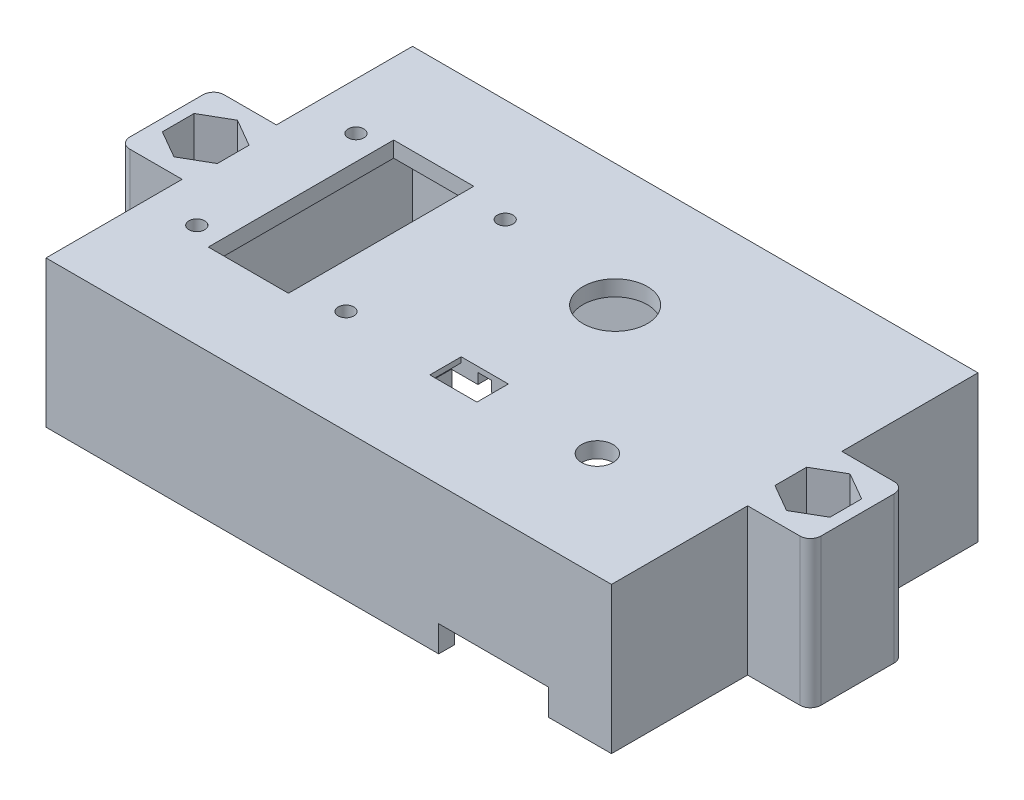
SolidWorks part; units mm, degrees
ref_plane "Front Plane" through (0, 0, 0) normal (0, 0, 1) x (1, 0, 0)
ref_plane "Top Plane" through (0, 0, 0) normal (0, 1, 0) x (1, 0, 0)
ref_plane "Right Plane" through (0, 0, 0) normal (1, 0, 0) x (0, 0, -1)
sketch "Sketch2" plane through (0, 0, 0) normal (0, 1, 0) x (1, 0, 0)
  line L0 (-37.0384, 33.0848) -> (37.9616, -5.9152) construction
  line L1 (-57.0384, 38.0848) -> (42.9616, 38.0848) construction
  line L2 (-57.0384, 38.0848) -> (-57.0384, -23.9152) construction
  line L3 (-57.0384, -23.9152) -> (42.9616, -23.9152) construction
  line L4 (42.9616, 38.0848) -> (42.9616, -23.9152) construction
  line L5 (-37.0384, -5.9152) -> (37.9616, 33.0848) construction
  line L6 (-57.0384, 7.0848) -> (-42.7957, 7.0848) construction
  line L7 (-58.0384, 39.0848) -> (43.9616, 39.0848) construction
  line L8 (-58.0384, 39.0848) -> (-58.0384, -24.9152) construction
  line L9 (-58.0384, -24.9152) -> (43.9616, -24.9152) construction
  line L10 (43.9616, 39.0848) -> (43.9616, -24.9152) construction
  line L11 (-61.0384, 42.0848) -> (46.9616, 42.0848)
  line L12 (-61.0384, 42.0848) -> (-61.0384, -27.9152)
  line L13 (-61.0384, -27.9152) -> (46.9616, -27.9152)
  line L14 (46.9616, 42.0848) -> (46.9616, -27.9152)
  line L15 (-25.0384, 0.0848) -> (-17.0384, 0.0848) construction
  line L16 (-25.0384, 0.0848) -> (-25.0384, -14.4152) construction
  line L17 (-25.0384, -14.4152) -> (-17.0384, -14.4152) construction
  line L18 (-17.0384, 0.0848) -> (-17.0384, -14.4152) construction
  line L19 (-19.0384, 3.5848) -> (-15.0384, 3.5848) construction
  line L20 (-19.0384, 3.5848) -> (-19.0384, 1.5848) construction
  line L21 (-19.0384, 1.5848) -> (-15.0384, 1.5848) construction
  line L22 (-15.0384, 3.5848) -> (-15.0384, 1.5848) construction
  line L23 (-17.0384, 1.5848) -> (-15.0384, 1.5848) construction
  line L24 (-17.0384, 1.5848) -> (-17.0384, -8.4152) construction
  line L25 (-17.0384, -8.4152) -> (-15.0384, -8.4152) construction
  line L26 (-15.0384, 1.5848) -> (-15.0384, -8.4152) construction
  line L28 (-54.5384, -10.6152) -> (-21.0384, -10.6152) construction
  line L29 (-54.5384, -10.6152) -> (-54.5384, 24.7848) construction
  line L30 (-54.5384, 24.7848) -> (-21.0384, 24.7848) construction
  line L31 (-21.0384, -10.6152) -> (-21.0384, 24.7848) construction
  point P4 (-37.0384, 33.0848)
  point P5 (37.9616, 33.0848)
  point P6 (37.9616, -5.9152)
  point P7 (-37.0384, -5.9152)
  point P9 (20.4616, 5.5848)
  point P28 (-54.5384, 7.0848)
  point P38 (-37.0384, 33.0848)
  dimension "D11" = 1.5
  dimension "D12" = 2
  dimension "D1" = 62
  dimension "D2" = 100
  dimension "D3" = 5
  dimension "D4" = 20
  dimension "D5" = 5
  dimension "D6" = 5
  dimension "D7" = 18
  dimension "D8" = 20
  dimension "D9" = 18
  dimension "D10" = 5
  dimension "D13" = 2
  dimension "D14" = 1
  dimension "D15" = 3
  dimension "D16" = 1
  dimension "D17" = 3
  dimension "D18" = 1
  dimension "D19" = 3
  dimension "D20" = 1
  dimension "D21" = 3
  dimension "D22" = 10.5
  dimension "D23" = 33
  dimension "D24" = 61
  dimension "D25" = 39
  dimension "D26" = 4
  dimension "D27" = 10
  dimension "D28" = 35.4
  dimension "D29" = 33.5
  dimension "D30" = 2.5
extrude "Boss-Extrude1" add sketch "Sketch2" along normal blind 3
sketch "Sketch7" plane through (0, 0, 0) normal (0, -1, 0) x (-1, 0, 0)
  line L0 (57.0384, -23.9152) -> (-42.9616, -23.9152) construction
  line L1 (55.0384, -14.9152) -> (58.0384, -14.9152) construction
  line L2 (58.0384, 39.0848) -> (-43.9616, 39.0848)
  line L3 (58.0384, 39.0848) -> (58.0384, -24.9152)
  line L4 (58.0384, -24.9152) -> (-43.9616, -24.9152)
  line L5 (-43.9616, 39.0848) -> (-43.9616, -24.9152)
  line L6 (61.0384, 42.0848) -> (-46.9616, 42.0848)
  line L7 (61.0384, 42.0848) -> (61.0384, -27.9152)
  line L8 (61.0384, -27.9152) -> (-46.9616, -27.9152)
  line L9 (-46.9616, 42.0848) -> (-46.9616, -27.9152)
  line L10 (55.0384, -14.9152) -> (55.0384, -24.9152) construction
  line L11 (55.0384, -24.9152) -> (58.0384, -24.9152) construction
  line L12 (58.0384, -14.9152) -> (58.0384, -24.9152) construction
  line L13 (47.0384, -21.9152) -> (55.0384, -21.9152) construction
  line L14 (47.0384, -21.9152) -> (47.0384, -24.9152) construction
  line L15 (47.0384, -24.9152) -> (55.0384, -24.9152) construction
  line L16 (55.0384, -21.9152) -> (55.0384, -24.9152) construction
  line L17 (57.0384, 38.0848) -> (57.0384, -23.9152) construction
  dimension "D1" = 2
  dimension "D2" = 2
  dimension "D3" = 8
  dimension "D4" = 10
extrude "Boss-Extrude4" add sketch "Sketch7" along normal blind 25 contours L7 L6 L9 L8
sketch "Sketch16" plane through (0, 0, 0) normal (0, -1, 0) x (1, 0, 0)
  line L1 (-17.0384, 8.4152) -> (-15.0384, 8.4152)
  line L2 (-17.0384, 8.4152) -> (-17.0384, -1.5848)
  line L3 (-17.0384, -1.5848) -> (-15.0384, -1.5848)
  line L4 (-15.0384, 8.4152) -> (-15.0384, -1.5848)
  line L5 (-15.0384, -1.5848) -> (-19.0384, -1.5848)
  line L6 (-15.0384, -1.5848) -> (-15.0384, -3.5848)
  line L7 (-15.0384, -3.5848) -> (-19.0384, -3.5848)
  line L8 (-19.0384, -1.5848) -> (-19.0384, -3.5848)
  line L9 (-55.0384, 14.9152) -> (-58.0384, 14.9152)
  line L10 (-55.0384, 14.9152) -> (-55.0384, 24.9152)
  line L11 (-55.0384, 24.9152) -> (-58.0384, 24.9152)
  line L12 (-58.0384, 14.9152) -> (-58.0384, 24.9152)
  line L13 (-55.0384, 21.9152) -> (-47.0384, 21.9152)
  line L14 (-55.0384, 21.9152) -> (-55.0384, 24.9152)
  line L15 (-55.0384, 24.9152) -> (-47.0384, 24.9152)
  line L16 (-47.0384, 21.9152) -> (-47.0384, 24.9152)
  line M7 (43.9616, 24.9152) -> (-58.0384, 24.9152)
  line M8 (-58.0384, 24.9152) -> (-58.0384, -39.0848)
extrude "Boss-Extrude5" add sketch "Sketch16" along normal offset from surface (22.8 mm away) 2.2 contours L4 L1 L2 L3 | L9 L10 M7 M8 | L13 L16 L10 M7 | L6 L7 L8 L5 up to face at (-7.0384, -25, -7.0848)
sketch "Sketch19" plane through (0, 0, 0) normal (0, -1, 0) x (1, 0, 0)
  line L1 (-55.5384, 2.6152) -> (-49.5384, 2.6152)
  line L2 (-55.5384, 2.6152) -> (-55.5384, -16.7848)
  line L3 (-55.5384, -16.7848) -> (-49.5384, -16.7848)
  line L4 (-49.5384, 2.6152) -> (-49.5384, -16.7848)
  line L5 (-57.0384, -7.0848) -> (-42.7957, -7.0848) construction
  line L6 (-54.5384, -24.7848) -> (-21.0384, -24.7848) construction
  line L7 (-54.5384, 10.6152) -> (-54.5384, -24.7848) construction
  point P6 (-55.5384, -7.0848)
  dimension "D1" = 8
  dimension "D2" = 6
  dimension "D3" = 5
extrude "Cut-Extrude10" cut sketch "Sketch19" against normal blind 1
sketch "Sketch18" plane through (0, 0, 0) normal (0, -1, 0) x (1, 0, 0)
  line L0 (-54.5384, 10.6152) -> (-54.5384, -24.7848) construction
  line L1 (-47.3384, -24.7848) -> (-32.0384, -24.7848)
  line L2 (-47.3384, -24.7848) -> (-47.3384, 10.6152)
  line L3 (-47.3384, 10.6152) -> (-32.0384, 10.6152)
  line L4 (-32.0384, -24.7848) -> (-32.0384, 10.6152)
  line L5 (-21.0384, 10.6152) -> (-21.0384, -24.7848) construction
  line L6 (-54.5384, -24.7848) -> (-21.0384, -24.7848) construction
  line L7 (-54.5384, 10.6152) -> (-21.0384, 10.6152) construction
  line L8 (-47.3384, -7.0848) -> (-57.0384, -7.0848) construction
  circle A0 centre (-52.0384, -22.2848) radius 1.5
  circle A1 centre (-23.5384, -22.2848) radius 1.5
  circle A2 centre (-23.5384, 8.1152) radius 1.5
  circle A3 centre (-52.0384, 8.1152) radius 1.5
  point P18 (-52.0384, 8.1152)
  point P19 (-23.5384, -22.2848)
  dimension "D3" = 2.5
  dimension "D5" = 3
  dimension "D1" = 7.2
  dimension "D2" = 11
  dimension "D4" = 2.5
  dimension "D6" = 2.5
  dimension "D7" = 2.5
  dimension "D8" = 2
  dimension "D9" = 2
extrude "Cut-Extrude9" cut sketch "Sketch18" against normal through all
sketch "Sketch20" plane through (0, 0, 0) normal (0, -1, 0) x (1, 0, 0)
  line L0 (-49.5384, 2.6152) -> (-55.5384, 2.6152) construction
  line L1 (-55.5384, 12.6152) -> (-49.5384, 12.6152)
  line L2 (-55.5384, 12.6152) -> (-55.5384, 2.6152)
  line L3 (-55.5384, 2.6152) -> (-49.5384, 2.6152)
  line L4 (-49.5384, 12.6152) -> (-49.5384, 2.6152)
  line L5 (-54.5384, 10.6152) -> (-54.5384, -24.7848) construction
  line L6 (-49.5384, -7.0848) -> (-56.0913, -7.0848) construction
  line L7 (-49.5384, -16.7848) -> (-49.5384, 2.6152) construction
  line L8 (-55.5384, -16.7848) -> (-49.5384, -16.7848)
  line L9 (-49.5384, -26.7848) -> (-49.5384, -16.7848)
  line L10 (-55.5384, -26.7848) -> (-49.5384, -26.7848)
  line L11 (-55.5384, -26.7848) -> (-55.5384, -16.7848)
  line L12 (-52.0384, 8.1152) -> (-23.5384, 8.1152) construction
  line L13 (-37.7884, 8.1152) -> (-37.7884, 15.0987) construction
  line L14 (-20.0384, -26.7848) -> (-20.0384, -16.7848)
  line L15 (-20.0384, -26.7848) -> (-26.0384, -26.7848)
  line L16 (-26.0384, -26.7848) -> (-26.0384, -16.7848)
  line L17 (-20.0384, -16.7848) -> (-26.0384, -16.7848)
  line L18 (-20.0384, 2.6152) -> (-26.0384, 2.6152)
  line L19 (-26.0384, 12.6152) -> (-26.0384, 2.6152)
  line L20 (-20.0384, 12.6152) -> (-26.0384, 12.6152)
  line L21 (-20.0384, 12.6152) -> (-20.0384, 2.6152)
  circle A0 centre (-52.0384, 8.1152) radius 1.5
  circle A1 centre (-23.5384, 8.1152) radius 2
  circle A2 centre (-52.0384, -22.2848) radius 2
  circle A3 centre (-23.5384, -22.2848) radius 2
  circle A4 centre (-52.0384, 8.1152) radius 1.5 construction
  dimension "D1" = 10
  dimension "D2" = 6
  dimension "D3" = 5
extrude "Boss-Extrude6" add sketch "Sketch20" along normal blind 1.5
sketch "Sketch21" plane through (0, 3, 0) normal (0, -1, 0) x (1, 0, 0)
  line L4 (-54.5384, 10.6152) -> (-21.0384, 10.6152) construction
  line L5 (-5.0384, 4.6152) -> (3.9616, 4.6152)
  line L6 (-5.0384, 4.6152) -> (-5.0384, 10.6152)
  line L7 (-5.0384, 10.6152) -> (3.9616, 10.6152)
  line L8 (3.9616, 4.6152) -> (3.9616, 10.6152)
  line L11 (-15.0384, -1.5848) -> (-15.0384, 8.4152) construction
  line L12 (-54.5384, -24.7848) -> (-21.0384, -24.7848) construction
  circle A0 centre (1.1116, -18.6348) radius 6.15
  circle A2 centre (23.9616, 7.6152) radius 3
  dimension "D1" = 12.3
  dimension "D5" = 20
  dimension "D2" = 6
  dimension "D3" = 9
  dimension "D4" = 10
extrude "Cut-Extrude11" cut sketch "Sketch21" along normal blind 1 contours L5 L8 L7 L6
sketch "Sketch23" plane through (0, 0, 0) normal (0, -1, 0) x (1, 0, 0)
  line L0 (-0.5384, 10.6152) -> (-0.5384, 4.6152) construction
  line L1 (-5.0384, 10.6152) -> (3.9616, 10.6152) construction
  line L2 (-5.0384, 4.6152) -> (3.9616, 4.6152) construction
  line L3 (-5.0384, 7.6152) -> (3.9616, 7.6152) construction
  line L4 (-5.0384, 4.6152) -> (-5.0384, 10.6152) construction
  line L5 (3.9616, 4.6152) -> (3.9616, 10.6152) construction
  line L6 (-0.5384, 10.6152) -> (-0.5384, 4.6152) construction
  line L7 (-6.9154, 10.6152) -> (5.8386, 10.6152)
  line L8 (-6.9154, 10.6152) -> (-6.9154, 4.6152)
  line L9 (-6.9154, 4.6152) -> (5.8386, 4.6152)
  line L10 (5.8386, 10.6152) -> (5.8386, 4.6152)
  line L11 (-6.9154, 7.6152) -> (5.8386, 7.6152) construction
  line L13 (-1.8519, 4.6152) -> (0.7751, 4.6152)
  line L14 (-1.8519, 4.6152) -> (-1.8519, 1.4882)
  line L15 (-1.8519, 1.4882) -> (0.7751, 1.4882)
  line L16 (0.7751, 4.6152) -> (0.7751, 1.4882)
  point P22 (-0.5384, 1.4882)
  dimension "D1" = 12.754
  dimension "D2" = 3.127
  dimension "D3" = 2.627
extrude "Cut-Extrude13" cut sketch "Sketch23" against normal up to vertex (2 mm away) contours L16 L9 L14 L15 | L10 L7 L8 L9
sketch "Sketch24" plane through (0, 3, 0) normal (0, 1, 0) x (1, 0, 0)
  circle A0 centre (1.1116, 18.6348) radius 6.15
  circle A1 centre (23.9616, -7.6152) radius 3
extrude "Cut-Extrude14" cut sketch "Sketch24" against normal through all
sketch "Sketch28" plane through (0, -25, 0) normal (0, -1, 0) x (1, 0, 0)
  line L0 (-61.0384, 27.9152) -> (46.9616, 27.9152) construction
  line L1 (13.9616, 27.9152) -> (34.9616, 27.9152)
  line L2 (13.9616, 27.9152) -> (13.9616, 24.9152)
  line L3 (13.9616, 24.9152) -> (34.9616, 24.9152)
  line L4 (34.9616, 27.9152) -> (34.9616, 24.9152)
  line L5 (-58.0384, 24.9152) -> (43.9616, 24.9152) construction
  line L6 (46.9616, -42.0848) -> (46.9616, 27.9152) construction
  line L7 (46.9616, -42.0848) -> (46.9616, 27.9152) construction
  dimension "D1" = 33
  dimension "D2" = 12
extrude "Cut-Extrude15" cut sketch "Sketch28" against normal blind 5
sketch "Sketch31" plane through (0, -25, 0) normal (0, -1, 0) x (1, 0, 0)
  line L0 (-61.0384, -42.0848) -> (-61.0384, 27.9152) construction
  line L1 (-61.0384, 1.9152) -> (-73.0384, 1.9152)
  line L2 (-61.0384, 1.9152) -> (-61.0384, -16.0848)
  line L3 (-61.0384, -16.0848) -> (-73.0384, -16.0848)
  line L4 (-73.0384, 1.9152) -> (-73.0384, -16.0848)
  line L6 (-7.0384, -42.0848) -> (-7.0384, -54.0736) construction
  line L7 (-61.0384, -42.0848) -> (46.9616, -42.0848) construction
  line L8 (46.9616, -16.0848) -> (58.9616, -16.0848)
  line L9 (58.9616, 1.9152) -> (58.9616, -16.0848)
  line L10 (46.9616, 1.9152) -> (58.9616, 1.9152)
  line L11 (46.9616, 1.9152) -> (46.9616, -16.0848)
  line L12 (46.9616, -42.0848) -> (46.9616, 27.9152) construction
  circle A0 centre (-65.5384, -7.0848) radius 3.25
  circle A1 centre (51.4616, -7.0848) radius 3.25
  point P6 (-61.0384, -7.0848)
  point P7 (-73.0384, -7.0848)
  dimension "D3" = 6.5
  dimension "D1" = 12
  dimension "D2" = 18
  dimension "D4" = 7.5
extrude "Boss-Extrude8" add sketch "Sketch31" against normal up to surface (28 mm away) up to face at (1.1116, 3, -12.4848)
fillet "Fillet1" radius 2 4 edges at (58.9616, -11, -16.0848) (58.9616, -11, 1.9152) (-73.0384, -11, -16.0848) (-73.0384, -11, 1.9152)
sketch "Sketch32" plane through (0, 3, 0) normal (0, 1, 0) x (1, 0, 0)
  line L0 (-61.0384, 42.0848) -> (-61.0384, -27.9152) construction
  line L1 (-60.2884, 4.0537) -> (-60.2884, 10.1159)
  line L2 (-60.2884, 10.1159) -> (-65.5384, 13.1469)
  line L3 (-65.5384, 13.1469) -> (-70.7884, 10.1159)
  line L4 (-70.7884, 10.1159) -> (-70.7884, 4.0537)
  line L5 (-70.7884, 4.0537) -> (-65.5384, 1.0226)
  line L6 (-65.5384, 1.0226) -> (-60.2884, 4.0537)
  line L8 (-7.0384, -27.9152) -> (-7.0384, -9.4417) construction
  line L9 (-61.0384, -27.9152) -> (46.9616, -27.9152) construction
  line L10 (51.4616, 1.0226) -> (46.2116, 4.0537)
  line L11 (56.7116, 4.0537) -> (51.4616, 1.0226)
  line L12 (56.7116, 10.1159) -> (56.7116, 4.0537)
  line L13 (51.4616, 13.1469) -> (56.7116, 10.1159)
  line L14 (46.2116, 10.1159) -> (51.4616, 13.1469)
  line L15 (46.2116, 4.0537) -> (46.2116, 10.1159)
  circle A0 centre (-65.5384, 7.0848) radius 5.25 construction
  dimension "D1" = 10.5
extrude "Cut-Extrude17" cut sketch "Sketch32" against normal blind 10
